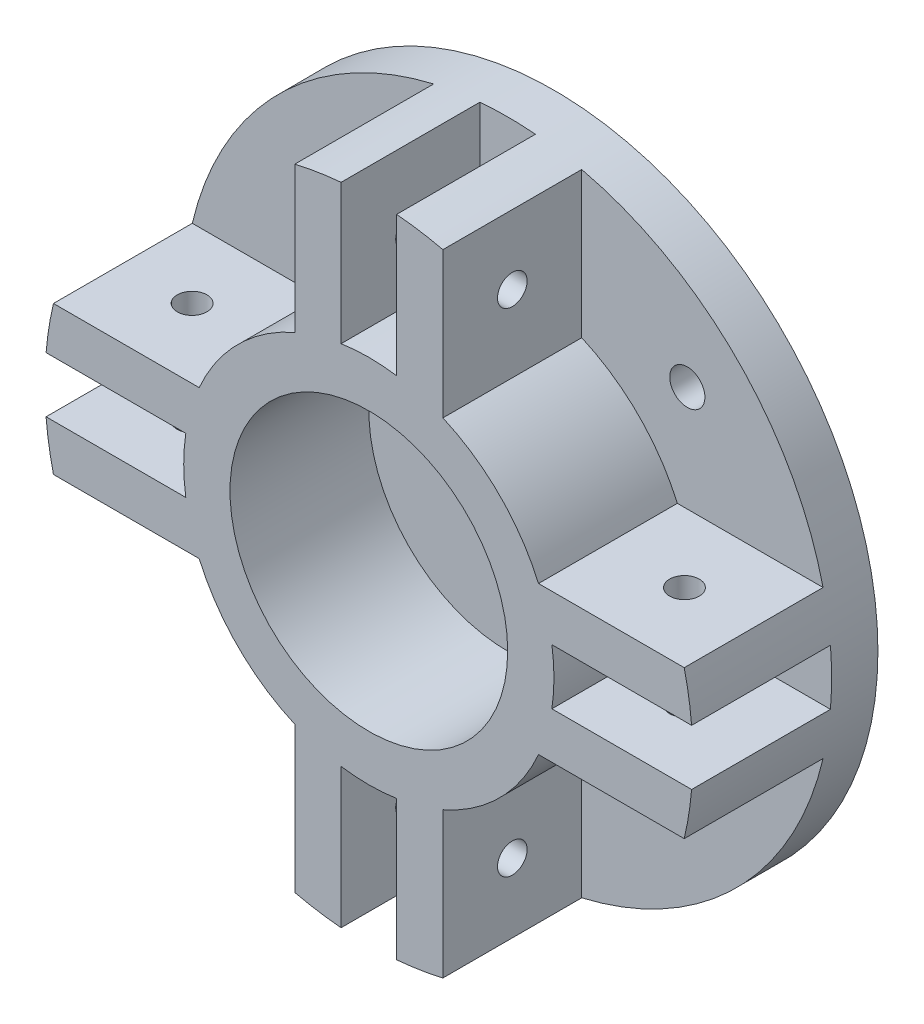
SolidWorks part; units mm, degrees
ref_plane "Front Plane" through (0, 0, 0) normal (0, 0, 1) x (1, 0, 0)
ref_plane "Top Plane" through (0, 0, 0) normal (0, 1, 0) x (1, 0, 0)
ref_plane "Right Plane" through (0, 0, 0) normal (1, 0, 0) x (0, 0, -1)
sketch "Sketch2" plane through (0, 0, 0) normal (0, 0, 1) x (1, 0, 0)
  circle A0 centre (0, 0) radius 5
  circle A1 centre (0, 0) radius 35
  dimension "D1" = 10
  dimension "D2" = 30
extrude "Boss-Extrude1" add sketch "Sketch2" along normal blind 5
sketch "Sketch3" plane through (0, 0, 5) normal (0, 0, 1) x (1, 0, 0)
  line L0 (0, 20) -> (0, 35) construction
  line L1 (3, 19.7737) -> (3, 34.8712)
  line L2 (-3, 19.7737) -> (3, 19.7737) construction
  line L3 (8, 18.3303) -> (8, 34.0735)
  line L4 (-8, 18.3303) -> (-8, 34.0735)
  line L5 (-3, 19.7737) -> (-3, 34.8712)
  line L6 (18.3303, 8) -> (34.0735, 8)
  line L7 (19.7737, 3) -> (34.8712, 3)
  line L8 (19.7737, -3) -> (34.8712, -3)
  line L9 (18.3303, -8) -> (34.0735, -8)
  line L10 (8, -18.3303) -> (8, -34.0735)
  line L11 (3, -19.7737) -> (3, -34.8712)
  line L12 (-3, -19.7737) -> (-3, -34.8712)
  line L13 (-8, -18.3303) -> (-8, -34.0735)
  line L14 (-18.3303, -8) -> (-34.0735, -8)
  line L15 (-19.7737, -3) -> (-34.8712, -3)
  line L16 (-19.7737, 3) -> (-34.8712, 3)
  line L17 (-18.3303, 8) -> (-34.0735, 8)
  circle A0 centre (0, 0) radius 15
  circle A1 centre (0, 0) radius 20
  circle A2 centre (0, 0) radius 35 construction
  arc A3 (3, 34.8712) -> (8, 34.0735) centre (0, 0) cw
  arc A4 (3, 19.7737) -> (8, 18.3303) centre (0, 0) cw
  arc A5 (-3, 34.8712) -> (-8, 34.0735) centre (0, 0) ccw
  arc A6 (-3, 19.7737) -> (-8, 18.3303) centre (0, 0) ccw
  arc A7 (34.8712, 3) -> (34.0735, 8) centre (0, 0) ccw
  arc A8 (34.8712, -3) -> (34.0735, -8) centre (0, 0) cw
  arc A9 (3, -34.8712) -> (8, -34.0735) centre (0, 0) ccw
  arc A10 (-3, -34.8712) -> (-8, -34.0735) centre (0, 0) cw
  arc A11 (-34.8712, -3) -> (-34.0735, -8) centre (0, 0) ccw
  arc A12 (-34.8712, 3) -> (-34.0735, 8) centre (0, 0) cw
  point P11 (0, 19.7737)
  point P26 (0, 0)
  point P49 (0, 0)
  circle M4 centre (0, 0) radius 35
  dimension "D5" = 30
  dimension "D2" = 5
  dimension "D3" = 3
  dimension "D1" = 5
  dimension "D4" = 4
extrude "Boss-Extrude3" add sketch "Sketch3" along normal blind 15 contours A1 L13 L12 M4 | A1 L11 L10 M4 | A1 L9 L8 M4 | A1 L7 L6 M4 | A1 L3 L1 M4 | A1 L5 L4 M4 | A1 L17 L16 M4 | A1 L15 L14 M4 | A1 A0
sketch "Sketch4" plane through (-8, 0, 0) normal (-1, 0, 0) x (0, 0, 1)
  circle A0 centre (12.5, 26.5963) radius 1.6
  dimension "D1" = 3.2
extrude "Cut-Extrude1" cut sketch "Sketch4" against normal through all
pattern_circular "CirPattern1" count 4 over 360 about axis through (0, 0, 20) along (0, 0, -1) of "Cut-Extrude1"
sketch "Sketch5" plane through (0, 0, 5) normal (0, 0, 1) x (1, 0, 0)
  circle A0 centre (19.4052, 19.4132) radius 1.9
  circle A1 centre (0, 0) radius 27.4488 construction
  circle A2 centre (-19.5258, -19.292) radius 1.25
  dimension "D1" = 3.8
  dimension "D2" = 2.5
extrude "Cut-Extrude2" cut sketch "Sketch5" against normal through all
